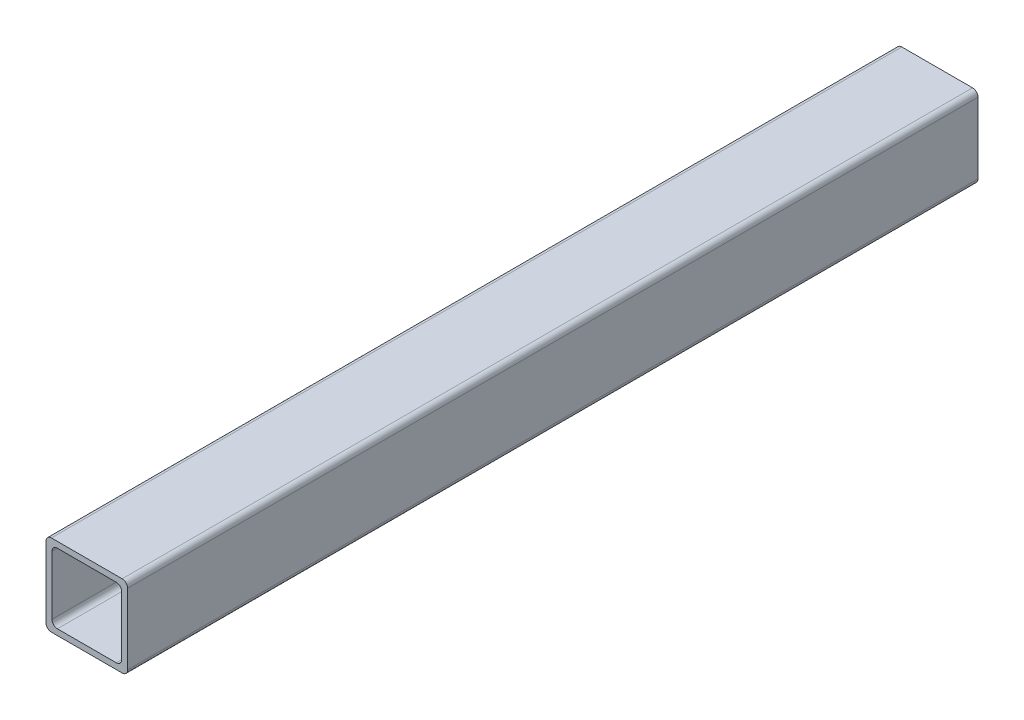
SolidWorks part; units mm, degrees
material "ASTM A500 Grade B Steel"
ref_plane "Front Plane" through (0, 0, 0) normal (0, 0, 1) x (1, 0, 0)
ref_plane "Top Plane" through (0, 0, 0) normal (0, 1, 0) x (1, 0, 0)
ref_plane "Right Plane" through (0, 0, 0) normal (1, 0, 0) x (0, 0, -1)
sketch "Sketch1" plane through (0, 0, 0) normal (0, 0, 1) x (1, 0, 0)
  line L0 (5.3086, -2.7686) -> (32.7914, -2.7686)
  line L1 (2.54, 0) -> (35.56, 0)
  line L2 (0, -2.54) -> (0, -35.56)
  line L3 (2.54, -38.1) -> (35.56, -38.1)
  line L4 (38.1, -2.54) -> (38.1, -35.56)
  line L5 (35.3314, -5.3086) -> (35.3314, -32.7914)
  line L6 (5.3086, -35.3314) -> (32.7914, -35.3314)
  line L7 (2.7686, -5.3086) -> (2.7686, -32.7914)
  line L8 (0, 0) -> (0, -38.1) construction
  line L9 (0, -38.1) -> (38.1, -38.1) construction
  line L10 (38.1, 0) -> (38.1, -38.1) construction
  line L11 (2.7686, -2.7686) -> (2.7686, -35.3314) construction
  line L12 (2.7686, -35.3314) -> (35.3314, -35.3314) construction
  line L13 (35.3314, -2.7686) -> (35.3314, -35.3314) construction
  line L14 (2.7686, -2.7686) -> (35.3314, -2.7686) construction
  line L15 (0, 0) -> (38.1, 0) construction
  arc A0 (0, -35.56) -> (2.54, -38.1) centre (2.54, -35.56) ccw
  arc A1 (38.1, -35.56) -> (35.56, -38.1) centre (35.56, -35.56) cw
  arc A2 (2.7686, -32.7914) -> (5.3086, -35.3314) centre (5.3086, -32.7914) ccw
  arc A3 (32.7914, -35.3314) -> (35.3314, -32.7914) centre (32.7914, -32.7914) ccw
  arc A4 (35.3314, -5.3086) -> (32.7914, -2.7686) centre (32.7914, -5.3086) ccw
  arc A5 (38.1, -2.54) -> (35.56, 0) centre (35.56, -2.54) ccw
  arc A6 (0, -2.54) -> (2.54, 0) centre (2.54, -2.54) cw
  arc A7 (5.3086, -2.7686) -> (2.7686, -5.3086) centre (5.3086, -5.3086) ccw
  point P12 (0, -38.1)
  dimension "D4" = 2.54
  dimension "D3" = 2.7686
extrude "Boss-Extrude1" add sketch "Sketch1" along normal blind 397
